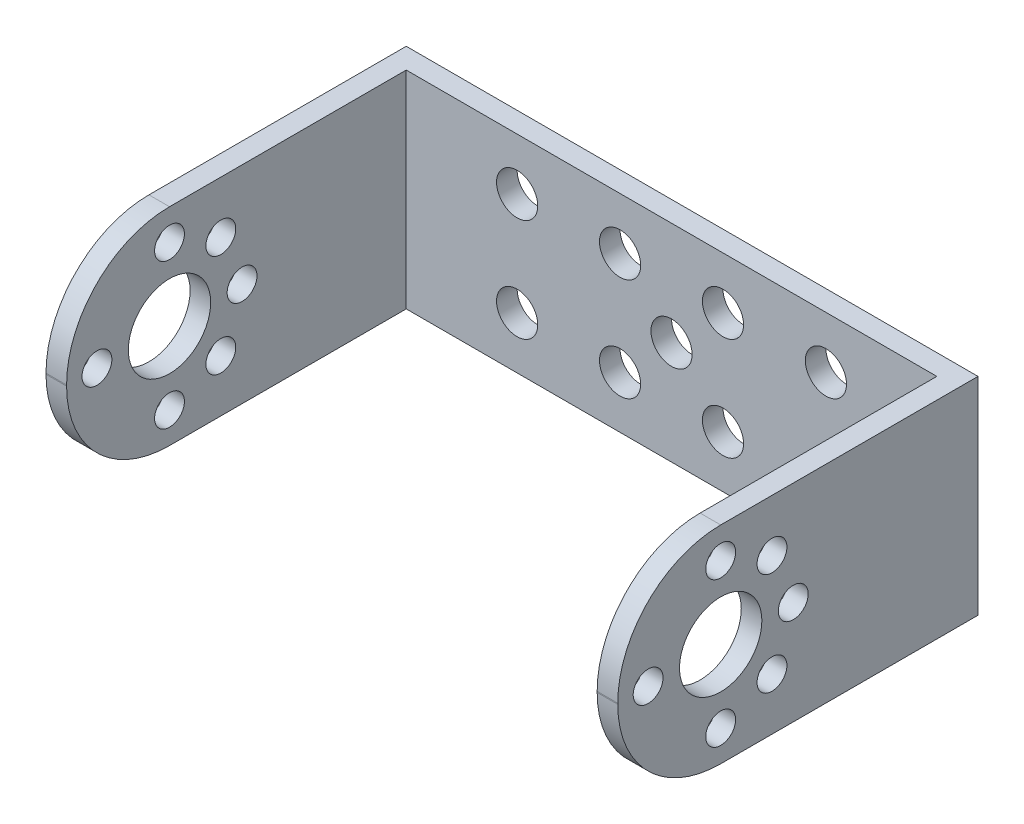
SolidWorks part; units mm, degrees
ref_plane "Alzado" through (0, 0, 0) normal (0, 0, 1) x (1, 0, 0)
ref_plane "Planta" through (0, 0, 0) normal (0, 1, 0) x (1, 0, 0)
ref_plane "Vista lateral" through (0, 0, 0) normal (1, 0, 0) x (0, 0, -1)
sketch "Croquis1" plane through (0, 0, 0) normal (0, 0, 1) x (1, 0, 0)
  line L1 (-27.775, -10.05) -> (27.775, -10.05)
  line L2 (-27.775, -10.05) -> (-27.775, 10.05)
  line L3 (-27.775, 10.05) -> (27.775, 10.05)
  line L4 (27.775, -10.05) -> (27.775, 10.05)
  line L5 (-27.775, -10.05) -> (27.775, 10.05) construction
  line L6 (-27.775, 10.05) -> (27.775, -10.05) construction
  point P0 (0, 0)
  dimension "D1" = 55.55
  dimension "D2" = 20.1
extrude "Saliente-Extruir1" add sketch "Croquis1" along normal blind 2
sketch "Croquis2" plane through (0, 0, 2) normal (0, 0, 1) x (1, 0, 0)
  line L0 (0, 15) -> (0, -15) construction
  line L1 (-34.5, 0) -> (34.5, 0) construction
  circle A1 centre (0, 0) radius 2
  circle A2 centre (5, 5) radius 2
  circle A3 centre (5, -5) radius 2
  circle A4 centre (-5, -5) radius 2
  circle A5 centre (-5, 5) radius 2
  circle A6 centre (15, 5) radius 2
  circle A7 centre (15, -5) radius 2
  circle A8 centre (-15, 5) radius 2
  circle A9 centre (-15, -5) radius 2
extrude "Cortar-Extruir1" cut sketch "Croquis2" against normal through all
sketch "Croquis3" plane through (0, 0, 0) normal (0, 0, 1) x (1, 0, 0)
  line L0 (-27.775, -10.05) -> (27.775, -10.05) construction
  line L1 (-27.775, 10.05) -> (-25.775, 10.05)
  line L2 (-27.775, 10.05) -> (-27.775, -10.05)
  line L3 (-27.775, -10.05) -> (-25.775, -10.05)
  line L4 (-25.775, 10.05) -> (-25.775, -10.05)
  line L6 (27.775, 10.05) -> (25.775, 10.05)
  line L7 (27.775, 10.05) -> (27.775, -10.05)
  line L8 (27.775, -10.05) -> (25.775, -10.05)
  line L9 (25.775, 10.05) -> (25.775, -10.05)
  dimension "D1" = 2
  dimension "D2" = 2
extrude "Saliente-Extruir2" add sketch "Croquis3" along normal blind 35
sketch "Croquis4" plane through (27.775, 0, 0) normal (1, 0, 0) x (0, 0, -1)
  line L0 (-35, 0) -> (0, 0) construction
  line L1 (-35, -10.05) -> (-35, 10.05) construction
  line L2 (-25, 0) -> (-25, -10.05) construction
  line L3 (-35, -10.05) -> (0, -10.05) construction
  line L4 (-25, 0) -> (-25, 10.05) construction
  line L5 (-35, 10.05) -> (0, 10.05) construction
  line L6 (-25, 0) -> (-18.4337, -6.5663) construction
  circle A0 centre (-25, 0) radius 4
  circle A1 centre (-32.05, 0) radius 1.45
  circle A2 centre (-17.95, 0) radius 1.45
  circle A4 centre (-20.0149, -4.9851) radius 1.45
  circle A5 centre (-25, -7.05) radius 1.45
  circle A6 centre (-25, 7.05) radius 1.45
  circle A7 centre (-20.0149, 4.9851) radius 1.45
  dimension "D1" = 8
  dimension "D2" = 10
  dimension "D3" = 2.9
  dimension "D4" = 2.95
extrude "Cortar-Extruir2" cut sketch "Croquis4" against normal up to surface (55.55 mm away) up to face at (-27.775, 0, 17.5)
fillet "Redondeo4" radius 10 4 edges at (-26.775, 10.05, 35) (-26.775, -10.05, 35) (26.775, 10.05, 35) (26.775, -10.05, 35)
